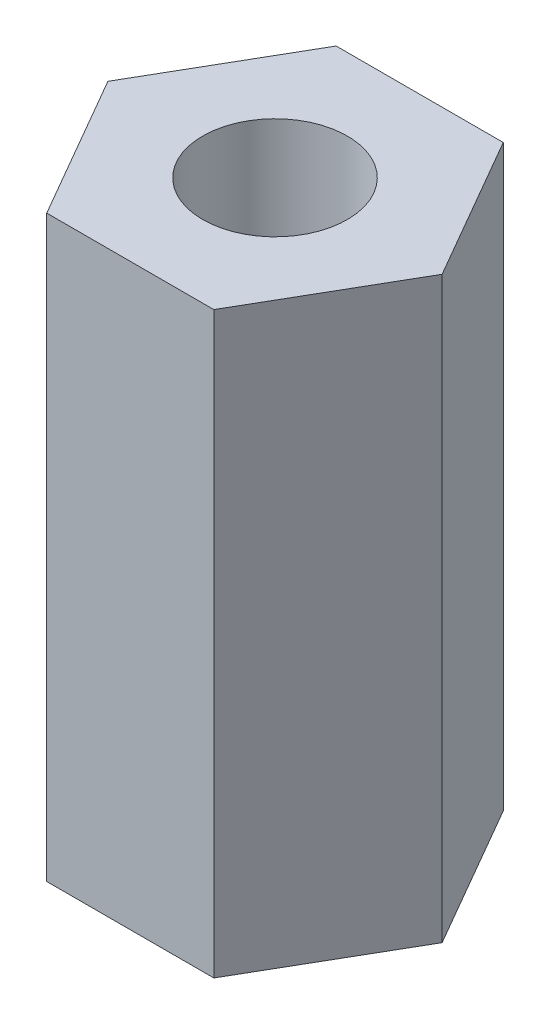
SolidWorks part; units mm, degrees
material "6061-T6 (SS)"
ref_plane "Front Plane" through (0, 0, 0) normal (0, 0, 1) x (1, 0, 0)
ref_plane "Top Plane" through (0, 0, 0) normal (0, 1, 0) x (1, 0, 0)
ref_plane "Right Plane" through (0, 0, 0) normal (1, 0, 0) x (0, 0, -1)
sketch "Sketch1" plane through (0, 0, 0) normal (0, 1, 0) x (1, 0, 0)
  line L1 (-3.6662, 6.35) -> (-7.3323, 0)
  line L2 (-7.3323, 0) -> (-3.6662, -6.35)
  line L3 (-3.6662, -6.35) -> (3.6662, -6.35)
  line L4 (3.6662, -6.35) -> (7.3323, 0)
  line L5 (7.3323, 0) -> (3.6662, 6.35)
  line L6 (3.6662, 6.35) -> (-3.6662, 6.35)
  circle A0 centre (0, 0) radius 6.35 construction
  circle A1 centre (0, 0) radius 3.175
  dimension "D2" = 6.35
  dimension "D1" = 12.7
extrude "Boss-Extrude1" add sketch "Sketch1" along normal blind 25.4
